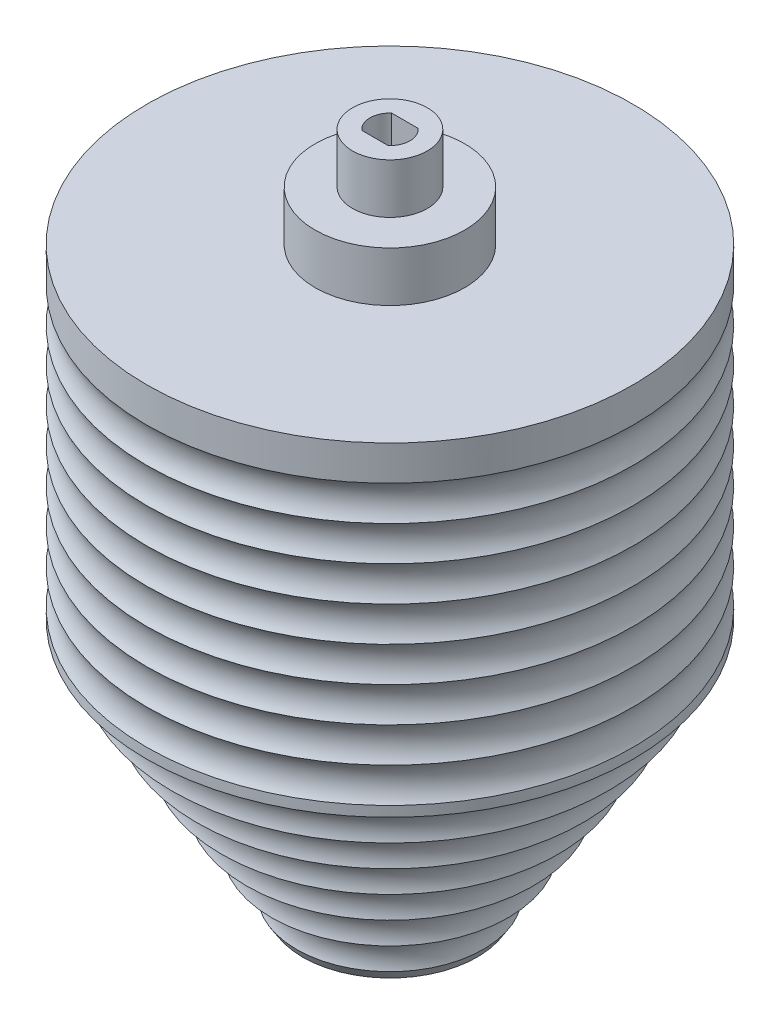
SolidWorks part; units mm, degrees
ref_plane "Front Plane" through (0, 0, 0) normal (0, 0, 1) x (1, 0, 0)
ref_plane "Top Plane" through (0, 0, 0) normal (0, 1, 0) x (1, 0, 0)
ref_plane "Right Plane" through (0, 0, 0) normal (1, 0, 0) x (0, 0, -1)
sketch "Sketch2" plane through (0, 0, 0) normal (0, 0, 1) x (1, 0, 0)
  line L0 (0, 57.3493) -> (0, -66.5497) construction
  line L1 (0, 45.2295) -> (-200, 45.2295)
  line L2 (-200, 45.2295) -> (-200, -104.7705)
  line L3 (-200, -104.7705) -> (-137.5, -204.7705)
  line L4 (-137.5, -204.7705) -> (-117.5, -204.7705)
  line L5 (-117.5, -204.7705) -> (-180, -104.7705)
  line L6 (-180, -104.7705) -> (-180, 25.2295)
  line L7 (-180, 25.2295) -> (-97.5, 25.2295)
  line L8 (0, 25.2295) -> (0, 45.2295)
  line L9 (-97.5, 25.2295) -> (-97.5, -104.7705)
  line L10 (-97.5, -104.7705) -> (-35, -204.7705)
  line L11 (-35, -204.7705) -> (0, -204.7705)
  line L12 (0, -204.7705) -> (0, 25.2295)
  dimension "D1" = 20
  dimension "D2" = 200
  dimension "D3" = 20
  dimension "D4" = 20
  dimension "D5" = 150
  dimension "D6" = 100
  dimension "D7" = 97.5
  dimension "D8" = 35
  dimension "D9" = 82.5
revolve "Revolve1" add sketch "Sketch2" angle 360 about L0
sketch "Sketch3" plane through (0, 0, 0) normal (0, 0, 1) x (1, 0, 0)
  line L0 (0, 80.7285) -> (0, -227.5722) construction
  line L1 (-97.5, 25.2295) -> (180, 25.2295) construction
  line L2 (-180, 25.2295) -> (180, 25.2295) construction
  circle A16 centre (-107.8608, 4.2503) radius 12.5
  circle A17 centre (-107.8608, -9.7358) radius 12.5
  circle A18 centre (-107.8608, -23.722) radius 12.5
  circle A19 centre (-107.8608, -37.7081) radius 12.5
  circle A20 centre (-107.8608, -51.6942) radius 12.5
  circle A21 centre (-107.8608, -65.6804) radius 12.5
  circle A22 centre (-107.8608, -79.6665) radius 12.5
  circle A23 centre (-107.8608, -93.6526) radius 12.5
  dimension "D2" = 25
  dimension "D1" = 97.5
revolve "Cut-Revolve1" cut sketch "Sketch3" angle 360 about L0
sketch "Sketch4" plane through (0, 0, 0) normal (0, 0, 1) x (1, 0, 0)
  line L2 (0, 86.0646) -> (0, -290.0279) construction
  circle A0 centre (-99.4467, -117.118) radius 12.5
  circle A1 centre (-89.4415, -133.1263) radius 12.5
  circle A2 centre (-79.4363, -149.1347) radius 12.5
  circle A3 centre (-69.431, -165.143) radius 12.5
  circle A4 centre (-59.4258, -181.1514) radius 12.5
  circle A5 centre (-49.4206, -197.1597) radius 12.5
  dimension "D1" = 25
revolve "Cut-Revolve2" cut sketch "Sketch4" angle 360 about L2
sketch "Sketch5" plane through (0, 45.2295, 0) normal (0, 1, 0) x (1, 0, 0)
  line L0 (-5.5226, 5.7879) -> (5.0522, 6.2028)
  line L2 (5.5226, -5.7879) -> (-5.0522, -6.2028)
  circle A0 centre (0, 0) radius 40
  arc A1 (-5.5226, 5.7879) -> (-5.0522, -6.2028) centre (0, 0) ccw
  arc A2 (5.5226, -5.7879) -> (5.0522, 6.2028) centre (0, 0) ccw
  dimension "D1" = 80
extrude "Boss-Extrude1" add sketch "Sketch5" along normal blind 22
sketch "Sketch6" plane through (0, 67.2295, 0) normal (0, 1, 0) x (1, 0, 0)
  circle A0 centre (0, 0) radius 25 construction
  circle A7 centre (0, 25) radius 2.5
  circle A8 centre (21.6506, 12.5) radius 2.5
  circle A9 centre (21.6506, -12.5) radius 2.5
  circle A10 centre (0, -25) radius 2.5
  circle A11 centre (-21.6506, -12.5) radius 2.5
  circle A12 centre (-21.6506, 12.5) radius 2.5
  point P19 (1.4277, -33.8565)
  point P20 (0, 0)
  dimension "D1" = 5
  dimension "D2" = 6
extrude "Cut-Extrude1" cut sketch "Sketch6" against normal blind 15
sketch "Sketch7" plane through (0, 0, 0) normal (0, 0, 1) x (1, 0, 0)
  line L0 (0, 169.9096) -> (0, -234.5825) construction
  line L1 (0, 25.2295) -> (125.172, 25.2295)
  line L2 (-180, 25.2295) -> (180, 25.2295) construction
  line L4 (125.172, 25.2295) -> (125.172, -129.0788)
  line L5 (125.172, -129.0788) -> (44.9325, -243.5299)
  line L6 (44.9325, -243.5299) -> (312.7482, -243.5299)
  line L7 (312.7482, -243.5299) -> (312.7482, 128.4363)
  line L8 (312.7482, 128.4363) -> (0, 128.4363)
  line L9 (0, 128.4363) -> (0, 25.2295)
revolve "Cut-Revolve3" cut sketch "Sketch7" angle 360 about L0
sketch "Sketch9" plane through (0, 25.2295, 0) normal (0, 1, 0) x (1, 0, 0)
  circle A0 centre (0, 0) radius 30
  dimension "D1" = 60
extrude "Boss-Extrude3" add sketch "Sketch9" along normal blind 20
sketch "Sketch8" plane through (0, 45.2295, 0) normal (0, 1, 0) x (1, 0, 0)
  line L0 (-5.2915, 6) -> (5.2915, 6)
  line L2 (5.2915, -6) -> (-5.2915, -6)
  line L3 (24.0019, 0) -> (-25.9172, 0) construction
  circle A0 centre (0, 0) radius 15
  arc A1 (5.2915, -6) -> (5.2915, 6) centre (0, 0) ccw
  arc A2 (-5.2915, 6) -> (-5.2915, -6) centre (0, 0) ccw
  dimension "D1" = 30
  dimension "D2" = 16
  dimension "D3" = 6
  dimension "D4" = 6
extrude "Boss-Extrude4" add sketch "Sketch8" along normal blind 20
sketch "Sketch10" plane through (0, 45.2295, 0) normal (0, 1, 0) x (1, 0, 0)
  circle A0 centre (0, 0) radius 8
extrude "Cut-Extrude2" cut sketch "Sketch10" against normal blind 3
